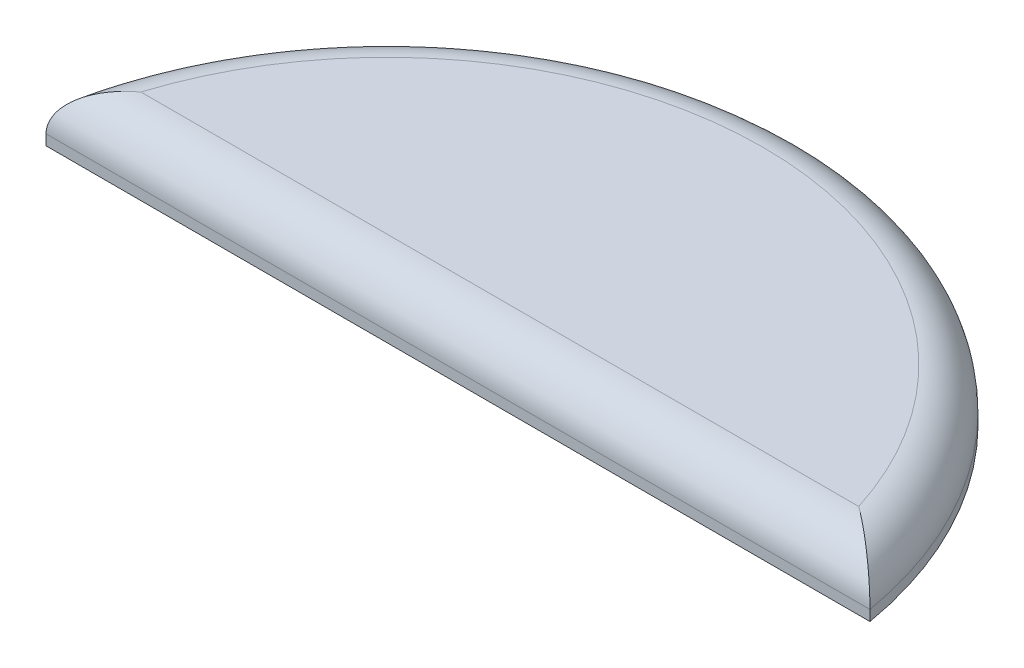
SolidWorks part; units mm, degrees
ref_plane "Front Plane" through (0, 0, 0) normal (0, 0, 1) x (1, 0, 0)
ref_plane "Top Plane" through (0, 0, 0) normal (0, 1, 0) x (1, 0, 0)
ref_plane "Right Plane" through (0, 0, 0) normal (1, 0, 0) x (0, 0, -1)
sketch "Sketch1" plane through (0, 0, 0) normal (0, 1, 0) x (1, 0, 0)
  line L0 (-41.9855, 0) -> (36.8445, 0)
  arc A0 (-41.9855, 0) -> (36.8445, 0) centre (-2.5705, -6.816) cw
  dimension "D2" = 40
  dimension "D1" = 78.83
extrude "Boss-Extrude1" add sketch "Sketch1" along normal blind 5
fillet "Fillet1" radius 4 2 edges at (-2.5705, 5, 0) (-2.5705, 5, -33.184)
